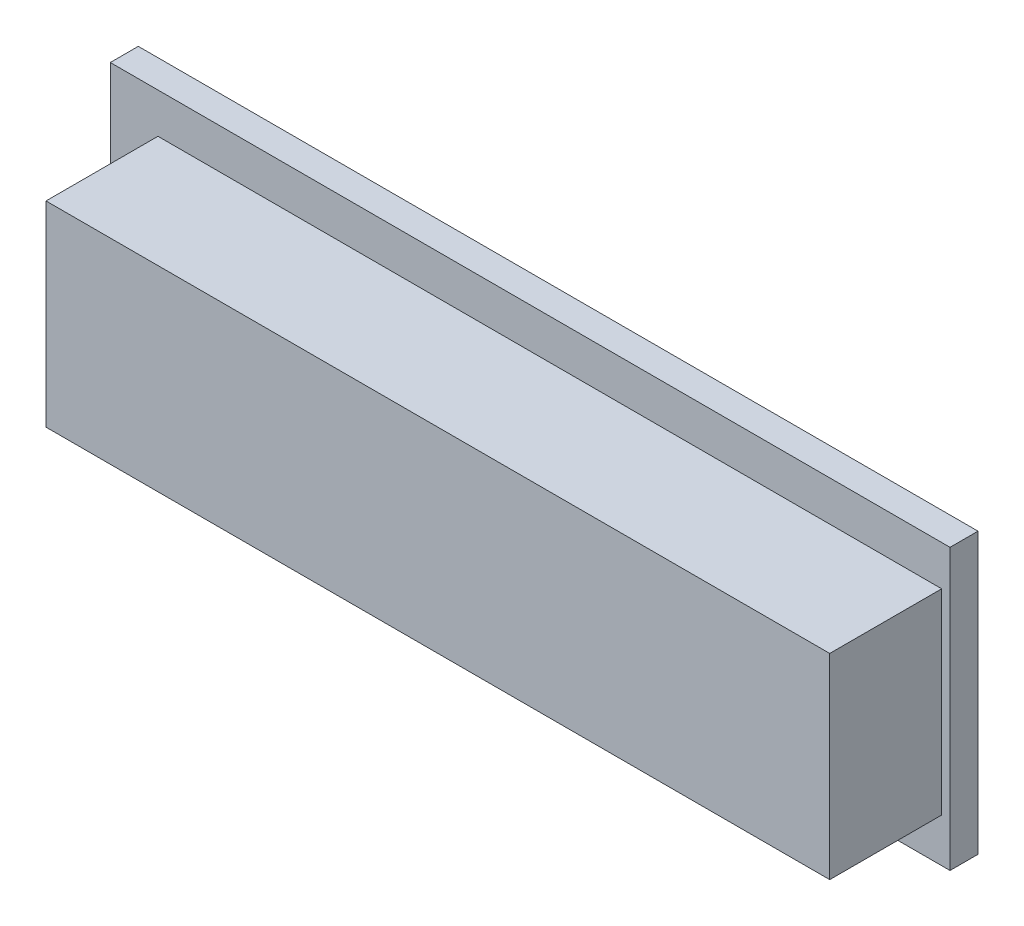
SolidWorks part; units mm, degrees
ref_plane "前视基准面" through (0, 0, 0) normal (0, 0, 1) x (1, 0, 0)
ref_plane "上视基准面" through (0, 0, 0) normal (0, 1, 0) x (1, 0, 0)
ref_plane "右视基准面" through (0, 0, 0) normal (1, 0, 0) x (0, 0, -1)
sketch "草图1" plane through (0, 0, 0) normal (0, 0, 1) x (1, 0, 0)
  line L1 (-40.0273, -2.2278) -> (-10.0273, -2.2278)
  line L2 (-40.0273, -2.2278) -> (-40.0273, -12.2278)
  line L3 (-40.0273, -12.2278) -> (-10.0273, -12.2278)
  line L4 (-10.0273, -2.2278) -> (-10.0273, -12.2278)
  line L5 (-40.0273, -2.2278) -> (-10.0273, -12.2278) construction
  line L6 (-40.0273, -12.2278) -> (-10.0273, -2.2278) construction
  point P0 (-25.0273, -7.2278)
  point P5 (-60.7664, -34.1304)
  point P6 (-25.0273, -7.2278)
  dimension "D1" = 30
  dimension "D2" = 10
extrude "凸台-拉伸1" add sketch "草图1" along normal blind 5
sketch "草图2" plane through (0, 0, 0) normal (0, 0, -1) x (-1, 0, 0)
  line L0 (18.389, -4.1596) -> (18.389, -10.1596)
  line L1 (11.589, -4.1596) -> (17.789, -4.1596)
  line L2 (11.589, -4.1596) -> (11.589, -10.1596)
  line L3 (11.589, -10.1596) -> (17.789, -10.1596)
  line L4 (17.789, -4.1596) -> (17.789, -10.1596)
  line L5 (11.589, -4.1596) -> (17.789, -10.1596) construction
  line L6 (11.589, -10.1596) -> (17.789, -4.1596) construction
  line L7 (18.389, -4.1596) -> (24.589, -4.1596)
  line L8 (24.589, -4.1596) -> (24.589, -10.1596)
  line L9 (18.389, -10.1596) -> (24.589, -10.1596)
  line L10 (25.189, -4.1596) -> (25.189, -10.1596)
  line L11 (25.189, -4.1596) -> (31.389, -4.1596)
  line L12 (31.389, -4.1596) -> (31.389, -10.1596)
  line L13 (25.189, -10.1596) -> (31.389, -10.1596)
  line L14 (31.989, -4.1596) -> (31.989, -10.1596)
  line L15 (31.989, -4.1596) -> (38.189, -4.1596)
  line L16 (38.189, -4.1596) -> (38.189, -10.1596)
  line L17 (31.989, -10.1596) -> (38.189, -10.1596)
  point P0 (14.689, -7.1596)
  point P5 (14.689, -7.1596)
  dimension "D1" = 6
  dimension "D2" = 6.2
  dimension "D4" = 0.6
  dimension "D3" = 4
extrude "切除-拉伸1" cut sketch "草图2" against normal blind 2
sketch "草图3" plane through (0, 0, 2) normal (0, 0, -1) x (-1, 0, 0)
  circle A0 centre (14.689, -7.1596) radius 1.5
  circle A1 centre (21.489, -7.1596) radius 1.5
  circle A2 centre (28.289, -7.1596) radius 1.5
  circle A3 centre (35.089, -7.1596) radius 1.5
  dimension "D1" = 3
extrude "切除-拉伸4" cut sketch "草图3" against normal blind 2
sketch "草图5" plane through (0, 0, 5) normal (0, 0, 1) x (1, 0, 0)
  line L4 (-10.0273, -12.2278) -> (-10.0273, -2.2278)
  line L5 (-10.0273, -2.2278) -> (-40.0273, -2.2278)
  line L6 (-40.0273, -2.2278) -> (-40.0273, -12.2278)
  line L7 (-40.0273, -12.2278) -> (-10.0273, -12.2278)
  line L8 (-10.0273, -12.2278) -> (-10.0273, -2.2278)
  line L9 (-10.0273, -2.2278) -> (-40.0273, -2.2278)
  line L10 (-40.0273, -2.2278) -> (-40.0273, -12.2278)
  line L11 (-40.0273, -12.2278) -> (-10.0273, -12.2278)
  line L41 (-38.3245, -3.6596) -> (-10.3245, -3.6596)
  line L42 (-38.3245, -3.6596) -> (-38.3245, -10.6596)
  line L43 (-38.3245, -10.6596) -> (-10.3245, -10.6596)
  line L44 (-10.3245, -3.6596) -> (-10.3245, -10.6596)
  line L45 (-38.3245, -3.6596) -> (-10.3245, -10.6596) construction
  line L46 (-38.3245, -10.6596) -> (-10.3245, -3.6596) construction
  point P1 (-24.3245, -7.1596)
  point P6 (-24.9864, -7.1596)
  point P18 (0, 0)
  dimension "D2" = 28
  dimension "D3" = 7
  dimension "D1" = 0
extrude "切除-拉伸5" cut sketch "草图5" against normal blind 4
